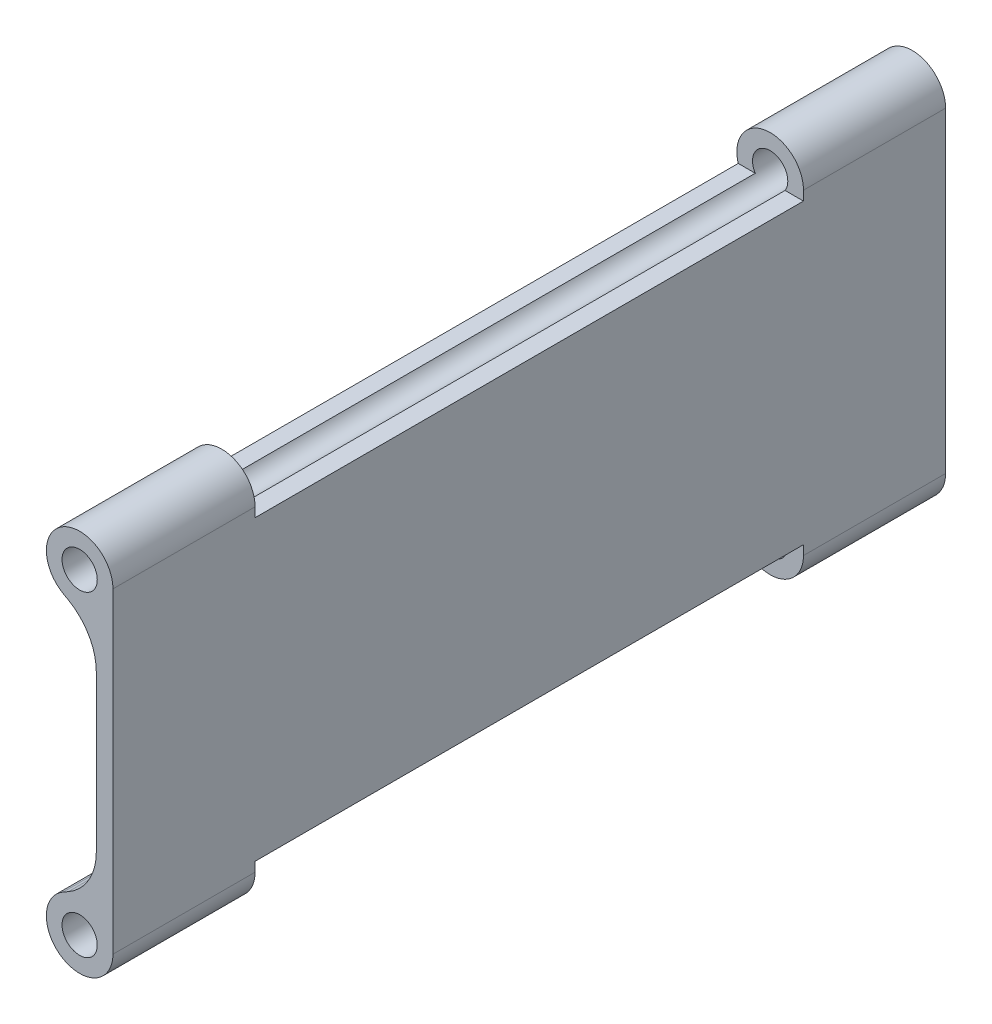
SolidWorks part; units mm, degrees
material "ABS"
ref_plane "Alzado" through (0, 0, 0) normal (0, 0, 1) x (1, 0, 0)
ref_plane "Planta" through (0, 0, 0) normal (0, 1, 0) x (1, 0, 0)
ref_plane "Vista lateral" through (0, 0, 0) normal (1, 0, 0) x (0, 0, -1)
sketch "Croquis1" plane through (0, 0, 0) normal (0, 0, 1) x (1, 0, 0)
  line L5 (-13.465, 0) -> (13.8234, 0) construction
  line L8 (-3, 19.8598) -> (-8.9869, 23.2963)
  line L9 (-3, 19.8598) -> (-3, -19.8598)
  line L10 (0, 28.5) -> (0, -28.5)
  line L11 (-3, -19.8598) -> (-8.9869, -23.2963)
  circle A0 centre (-6, 28.5) radius 3.175
  arc A5 (0, 28.5) -> (-8.9869, 23.2963) centre (-6, 28.5) ccw
  arc A6 (0, -28.5) -> (-8.9869, -23.2963) centre (-6, -28.5) cw
  circle A7 centre (-6, -28.5) radius 3.175
  point P7 (0, 0)
  point P15 (0, 0)
  point P16 (-3, 0)
  point P17 (-3, 0)
  dimension "D1" = 6.35
  dimension "D2" = 57
  dimension "D3" = 3
  dimension "D4" = 6
extrude "Saliente-Extruir1" add sketch "Croquis1" against normal blind 150
fillet "Redondeo1" radius 10 2 edges at (-3, -19.8598, -75) (-3, 19.8598, -75)
sketch "Croquis3" plane through (0, 0, 0) normal (1, 0, 0) x (0, 0, -1)
  line L0 (0, 0) -> (150, 0) construction
  line L1 (25.6041, 44.9478) -> (124.3959, 44.9478)
  line L2 (25.6041, 44.9478) -> (25.6041, 26.8024)
  line L3 (25.6041, 26.8024) -> (124.3959, 26.8024)
  line L4 (124.3959, 44.9478) -> (124.3959, 26.8024)
  line L5 (124.3959, -44.9478) -> (124.3959, -26.8024)
  line L6 (25.6041, -26.8024) -> (124.3959, -26.8024)
  line L7 (25.6041, -44.9478) -> (25.6041, -26.8024)
  line L8 (25.6041, -44.9478) -> (124.3959, -44.9478)
  line L9 (150, 14.0695) -> (150, -14.0695) construction
  point P16 (75, 0)
  point P17 (75, -26.8024)
extrude "Cortar-Extruir2" cut sketch "Croquis3" against normal through all
